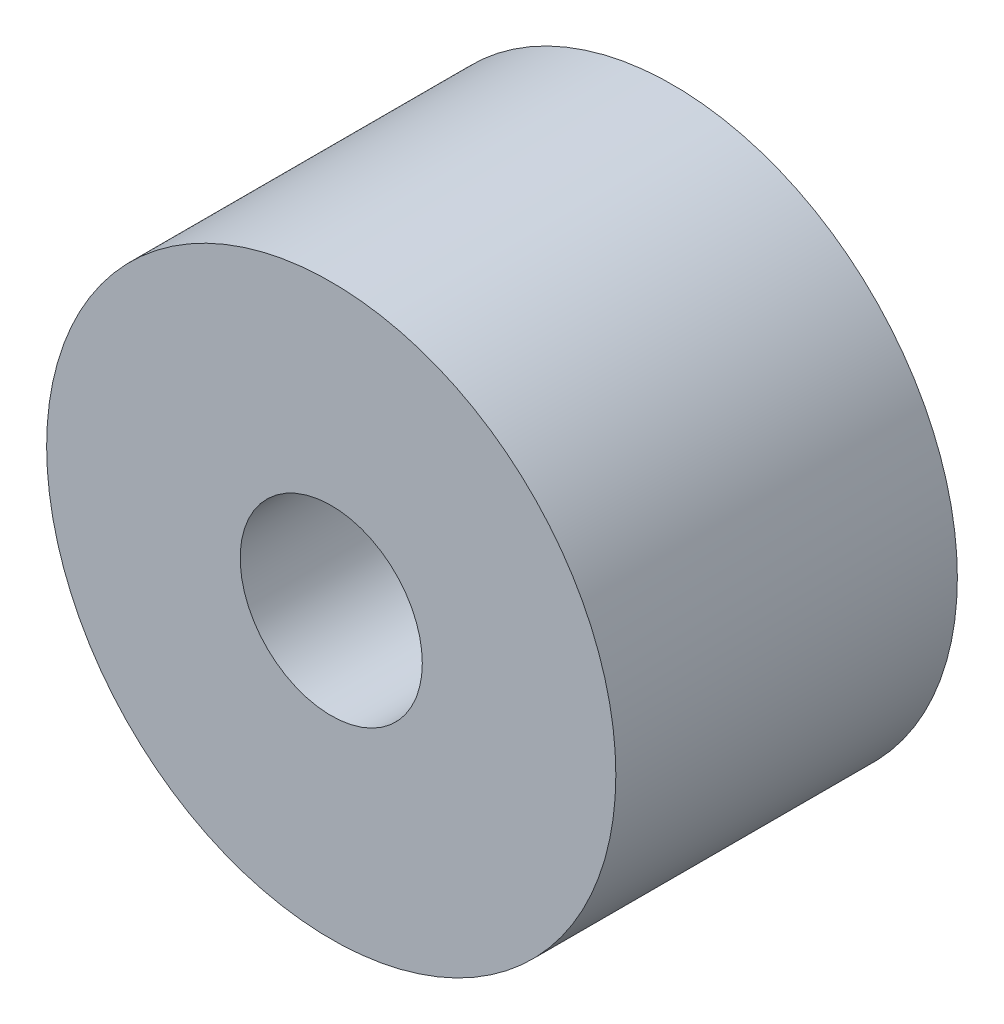
SolidWorks part; units mm, degrees
ref_plane "Front Plane" through (0, 0, 0) normal (0, 0, 1) x (1, 0, 0)
ref_plane "Top Plane" through (0, 0, 0) normal (0, 1, 0) x (1, 0, 0)
ref_plane "Right Plane" through (0, 0, 0) normal (1, 0, 0) x (0, 0, -1)
sketch "Sketch1" plane through (0, 0, 0) normal (0, 0, 1) x (1, 0, 0)
  circle A0 centre (0, 0) radius 5
  circle A1 centre (0, 0) radius 1.6
extrude "Grommet" add sketch "Sketch1" along normal blind 6
